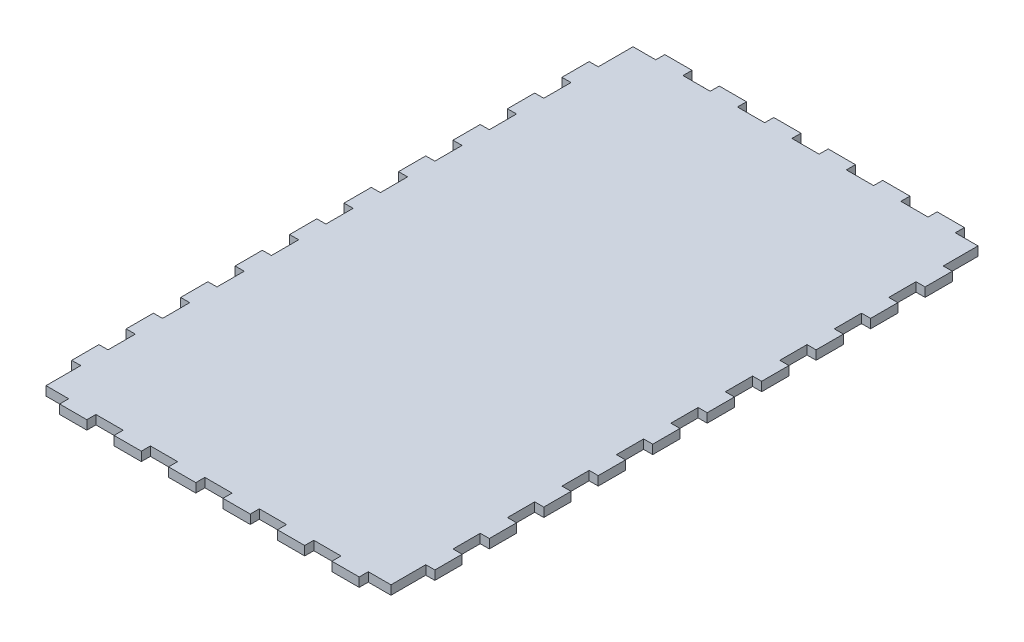
SolidWorks part; units mm, degrees
ref_plane "Front Plane" through (0, 0, 0) normal (0, 0, 1) x (1, 0, 0)
ref_plane "Top Plane" through (0, 0, 0) normal (0, 1, 0) x (1, 0, 0)
ref_plane "Right Plane" through (0, 0, 0) normal (1, 0, 0) x (0, 0, -1)
sketch "Sketch1" plane through (0, 0, 0) normal (0, 1, 0) x (1, 0, 0)
  line L0 (49.5, 100) -> (40.5, 100)
  line L1 (40.5, 100) -> (40.5, 97)
  line L2 (40.5, 97) -> (31.5, 97)
  line L3 (31.5, 97) -> (31.5, 100)
  line L4 (31.5, 100) -> (22.5, 100)
  line L5 (22.5, 100) -> (22.5, 97)
  line L6 (22.5, 97) -> (13.5, 97)
  line L7 (13.5, 97) -> (13.5, 100)
  line L8 (13.5, 100) -> (4.5, 100)
  line L9 (4.5, 100) -> (4.5, 97)
  line L10 (4.5, 97) -> (-4.5, 97)
  line L11 (-4.5, 97) -> (-4.5, 100)
  line L12 (-4.5, 100) -> (-13.5, 100)
  line L13 (-13.5, 100) -> (-13.5, 97)
  line L14 (-13.5, 97) -> (-22.5, 97)
  line L15 (-22.5, 97) -> (-22.5, 100)
  line L16 (-22.5, 100) -> (-31.5, 100)
  line L17 (-31.5, 100) -> (-31.5, 97)
  line L18 (-31.5, 97) -> (-40.5, 97)
  line L19 (-40.5, 97) -> (-40.5, 100)
  line L20 (-40.5, 100) -> (-49.5, 100)
  line L21 (-49.5, 100) -> (-49.5, 97)
  line L22 (-49.5, 97) -> (-57, 97)
  line L23 (-57, 97) -> (-57, 85.5)
  line L24 (-57, 85.5) -> (-60, 85.5)
  line L25 (-60, 85.5) -> (-60, 76.5)
  line L26 (-60, 76.5) -> (-57, 76.5)
  line L27 (-57, 76.5) -> (-57, 67.5)
  line L28 (-57, 67.5) -> (-60, 67.5)
  line L29 (-60, 67.5) -> (-60, 58.5)
  line L30 (-60, 58.5) -> (-57, 58.5)
  line L31 (-57, 58.5) -> (-57, 49.5)
  line L32 (-57, 49.5) -> (-60, 49.5)
  line L33 (-60, 49.5) -> (-60, 40.5)
  line L34 (-60, 40.5) -> (-57, 40.5)
  line L35 (-57, 40.5) -> (-57, 31.5)
  line L36 (-57, 31.5) -> (-60, 31.5)
  line L37 (-60, 31.5) -> (-60, 22.5)
  line L38 (-60, 22.5) -> (-57, 22.5)
  line L39 (-57, 22.5) -> (-57, 13.5)
  line L40 (-57, 13.5) -> (-60, 13.5)
  line L41 (-60, 13.5) -> (-60, 4.5)
  line L42 (-60, 4.5) -> (-57, 4.5)
  line L43 (-57, 4.5) -> (-57, -4.5)
  line L44 (-57, -4.5) -> (-60, -4.5)
  line L45 (-60, -4.5) -> (-60, -13.5)
  line L46 (-60, -13.5) -> (-57, -13.5)
  line L47 (-57, -13.5) -> (-57, -22.5)
  line L48 (-57, -22.5) -> (-60, -22.5)
  line L49 (-60, -22.5) -> (-60, -31.5)
  line L50 (-60, -31.5) -> (-57, -31.5)
  line L51 (-57, -31.5) -> (-57, -40.5)
  line L52 (-57, -40.5) -> (-60, -40.5)
  line L53 (-60, -40.5) -> (-60, -49.5)
  line L54 (-60, -49.5) -> (-57, -49.5)
  line L55 (-57, -49.5) -> (-57, -58.5)
  line L56 (-57, -58.5) -> (-60, -58.5)
  line L57 (-60, -58.5) -> (-60, -67.5)
  line L58 (-60, -67.5) -> (-57, -67.5)
  line L59 (-57, -67.5) -> (-57, -76.5)
  line L60 (-57, -76.5) -> (-60, -76.5)
  line L61 (-60, -76.5) -> (-60, -85.5)
  line L62 (-60, -85.5) -> (-57, -85.5)
  line L63 (-57, -85.5) -> (-57, -97)
  line L64 (-57, -97) -> (-49.5, -97)
  line L65 (-49.5, -97) -> (-49.5, -100)
  line L66 (-49.5, -100) -> (-40.5, -100)
  line L67 (-40.5, -100) -> (-40.5, -97)
  line L68 (-40.5, -97) -> (-31.5, -97)
  line L69 (-31.5, -97) -> (-31.5, -100)
  line L70 (-31.5, -100) -> (-22.5, -100)
  line L71 (-22.5, -100) -> (-22.5, -97)
  line L72 (-22.5, -97) -> (-13.5, -97)
  line L73 (-13.5, -97) -> (-13.5, -100)
  line L74 (-13.5, -100) -> (-4.5, -100)
  line L75 (-4.5, -100) -> (-4.5, -97)
  line L76 (-4.5, -97) -> (4.5, -97)
  line L77 (4.5, -97) -> (4.5, -100)
  line L78 (4.5, -100) -> (13.5, -100)
  line L79 (13.5, -100) -> (13.5, -97)
  line L80 (13.5, -97) -> (22.5, -97)
  line L81 (22.5, -97) -> (22.5, -100)
  line L82 (22.5, -100) -> (31.5, -100)
  line L83 (31.5, -100) -> (31.5, -97)
  line L84 (31.5, -97) -> (40.5, -97)
  line L85 (40.5, -97) -> (40.5, -100)
  line L86 (40.5, -100) -> (49.5, -100)
  line L87 (49.5, -100) -> (49.5, -97)
  line L88 (49.5, -97) -> (57, -97)
  line L89 (57, -97) -> (57, -85.5)
  line L90 (57, -85.5) -> (60, -85.5)
  line L91 (60, -85.5) -> (60, -76.5)
  line L92 (60, -76.5) -> (57, -76.5)
  line L93 (57, -76.5) -> (57, -67.5)
  line L94 (57, -67.5) -> (60, -67.5)
  line L95 (60, -67.5) -> (60, -58.5)
  line L96 (60, -58.5) -> (57, -58.5)
  line L97 (57, -58.5) -> (57, -49.5)
  line L98 (57, -49.5) -> (60, -49.5)
  line L99 (60, -49.5) -> (60, -40.5)
  line L100 (60, -40.5) -> (57, -40.5)
  line L101 (57, -40.5) -> (57, -31.5)
  line L102 (57, -31.5) -> (60, -31.5)
  line L103 (60, -31.5) -> (60, -22.5)
  line L104 (60, -22.5) -> (57, -22.5)
  line L105 (57, -22.5) -> (57, -13.5)
  line L106 (57, -13.5) -> (60, -13.5)
  line L107 (60, -13.5) -> (60, -4.5)
  line L108 (60, -4.5) -> (57, -4.5)
  line L109 (57, -4.5) -> (57, 4.5)
  line L110 (57, 4.5) -> (60, 4.5)
  line L111 (60, 4.5) -> (60, 13.5)
  line L112 (60, 13.5) -> (57, 13.5)
  line L113 (57, 13.5) -> (57, 22.5)
  line L114 (57, 22.5) -> (60, 22.5)
  line L115 (60, 22.5) -> (60, 31.5)
  line L116 (60, 31.5) -> (57, 31.5)
  line L117 (57, 31.5) -> (57, 40.5)
  line L118 (57, 40.5) -> (60, 40.5)
  line L119 (60, 40.5) -> (60, 49.5)
  line L120 (60, 49.5) -> (57, 49.5)
  line L121 (57, 49.5) -> (57, 58.5)
  line L122 (57, 58.5) -> (60, 58.5)
  line L123 (60, 58.5) -> (60, 67.5)
  line L124 (60, 67.5) -> (57, 67.5)
  line L125 (57, 67.5) -> (57, 76.5)
  line L126 (57, 76.5) -> (60, 76.5)
  line L127 (60, 76.5) -> (60, 85.5)
  line L128 (60, 85.5) -> (57, 85.5)
  line L129 (57, 85.5) -> (57, 97)
  line L130 (57, 97) -> (49.5, 97)
  line L131 (49.5, 97) -> (49.5, 100)
  line L132 (-49.5, 100) -> (-60, 100) construction
  line L133 (-60, 100) -> (-60, 85.5) construction
  line L134 (49.5, -100) -> (60, -100) construction
  line L135 (60, -100) -> (60, -85.5) construction
  line L136 (-60, 100) -> (60, -100) construction
  point P132 (0, 0)
extrude "Boss-Extrude1" add sketch "Sketch1" along normal mid plane 3
sketch "Sketch2" plane through (0, 1.5, 0) normal (0, 1, 0) x (1, 0, 0)
  text T0 "Top/Bottom\r\n"
extrude "Cut-Extrude1" [suppressed] cut sketch "Sketch2" against normal blind 1
